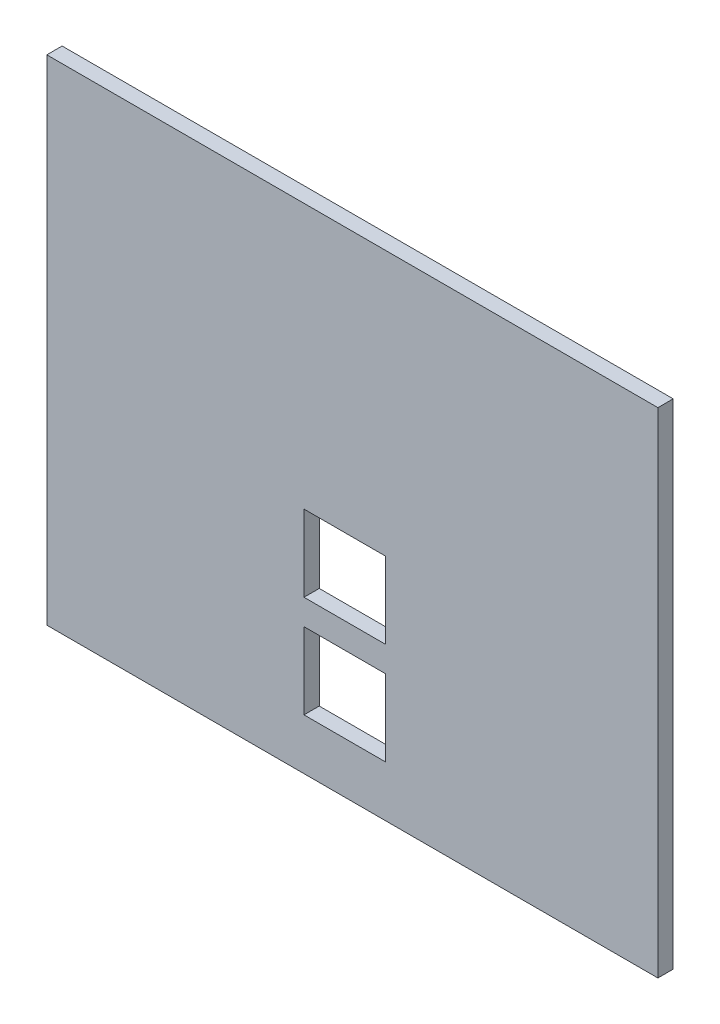
SolidWorks part; units mm, degrees
ref_plane "Plano frontal" through (0, 0, 0) normal (0, 0, 1) x (1, 0, 0)
ref_plane "Plano superior" through (0, 0, 0) normal (0, 1, 0) x (1, 0, 0)
ref_plane "Plano direito" through (0, 0, 0) normal (1, 0, 0) x (0, 0, -1)
sketch "Esboço1" plane through (0, 0, 0) normal (0, 0, 1) x (1, 0, 0)
  line L1 (60, -48.5) -> (-60, -48.5)
  line L2 (60, -48.5) -> (60, 48.5)
  line L3 (60, 48.5) -> (-60, 48.5)
  line L4 (-60, -48.5) -> (-60, 48.5)
  line L5 (60, -48.5) -> (-60, 48.5) construction
  line L6 (60, 48.5) -> (-60, -48.5) construction
  point P0 (0, 0)
  dimension "D1" = 120
  dimension "D2" = 97
extrude "Ressalto-extrusão1" add sketch "Esboço1" along normal blind 3
sketch "Esboço2" plane through (0, 0, 3) normal (0, 0, 1) x (1, 0, 0)
  line L0 (-60, -48.5) -> (60, -48.5) construction
  line L1 (-9.5, -23.5) -> (6.5, -23.5)
  line L2 (-9.5, -23.5) -> (-9.5, -38.5)
  line L3 (-9.5, -38.5) -> (6.5, -38.5)
  line L4 (6.5, -23.5) -> (6.5, -38.5)
  line L5 (60, -48.5) -> (60, 48.5) construction
  dimension "D1" = 15
  dimension "D2" = 16
  dimension "D3" = 10
  dimension "D4" = 53.5
extrude "Corte-extrusão1" cut sketch "Esboço2" against normal through all
pattern_linear "Padrão linear1" count 2 spacing 20 along (0, 1, 0) of "Corte-extrusão1"
